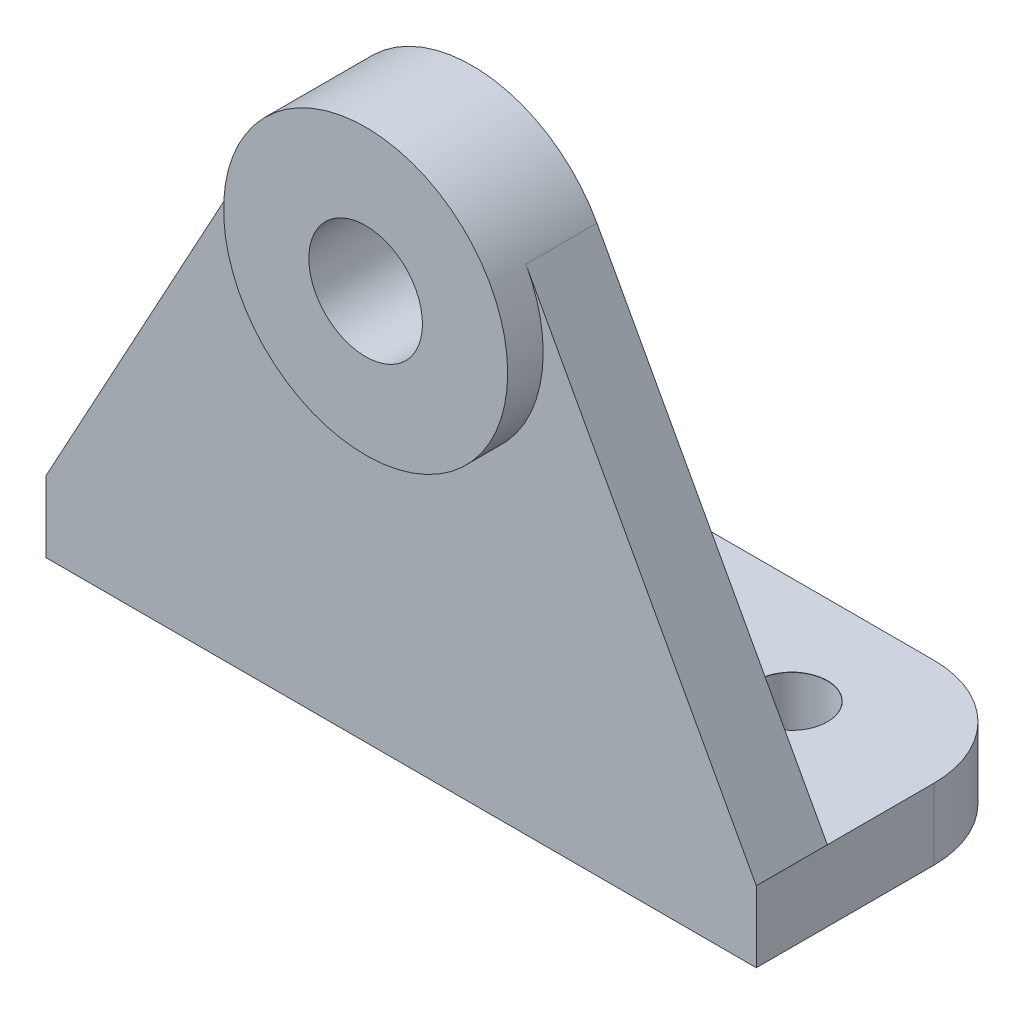
SolidWorks part; units mm, degrees
material "AISI 304"
ref_plane "Front Plane" through (0, 0, 0) normal (0, 0, 1) x (1, 0, 0)
ref_plane "Top Plane" through (0, 0, 0) normal (0, 1, 0) x (1, 0, 0)
ref_plane "Right Plane" through (0, 0, 0) normal (1, 0, 0) x (0, 0, -1)
sketch "Croquis1" plane through (0, 0, 0) normal (0, 1, 0) x (1, 0, 0)
  line L1 (50, -20) -> (-50, -20)
  line L2 (50, -20) -> (50, 20)
  line L3 (50, 20) -> (-50, 20)
  line L4 (-50, -20) -> (-50, 20)
  line L5 (50, -20) -> (-50, 20) construction
  line L6 (50, 20) -> (-50, -20) construction
  point P0 (0, 0)
  dimension "D1" = 40
  dimension "D2" = 100
extrude "Saliente-Extruir1" add sketch "Croquis1" along normal blind 10
sketch "Croquis2" plane through (0, 0, 20) normal (0, 0, 1) x (1, 0, 0)
  line L0 (0, 10) -> (0, 60) construction
  line L1 (-50, 10) -> (50, 10) construction
  line L2 (-50, 10) -> (-17.5647, 69.5647)
  line L3 (-50, 10) -> (50, 10)
  line L4 (50, 10) -> (17.5647, 69.5647)
  arc A0 (17.5647, 69.5647) -> (-17.5647, 69.5647) centre (0, 60) ccw
  circle A1 centre (0, 60) radius 8
  dimension "D2" = 20
  dimension "D3" = 16
  dimension "D1" = 50
extrude "Saliente-Extruir2" add sketch "Croquis2" against normal blind 10
sketch "Croquis3" plane through (0, 0, 20) normal (0, 0, 1) x (1, 0, 0)
  circle A0 centre (0, 60) radius 20
  circle A1 centre (0, 60) radius 8
extrude "Saliente-Extruir3" add sketch "Croquis3" along normal blind 5
sketch "Croquis4" plane through (0, 10, 0) normal (0, 1, 0) x (1, 0, 0)
  line L0 (-17.5647, -20) -> (-50, -20) construction
  circle A0 centre (-30, 5) radius 5.0987
  point P0 (-30, 5)
  point P7 (-30, 5)
  point P9 (-30, 5)
  dimension "D1" = 30
  dimension "D2" = 25
hole_wizard "Ø9.8 (9.8) Diameter Hole1" positions "Croquis4" profile "Croquis5" hole size "Ø9.8" standard "ANSI Metric" end condition through all
sketch "Croquis5" plane through (-30, 10, -5) normal (1, 0, 0) x (0, 0, 1)
  line L0 (0, 0) -> (0, 10)
  line L1 (0, 10) -> (4.9, 10)
  line L2 (4.9, 10) -> (4.9, 0.021)
  line L3 (4.9, 0.021) -> (4.925, 0)
  line L5 (4.925, 0) -> (0, 0)
  line L6 (-4.9, 0.021) -> (-4.925, 0) construction
  line L11 (0, -6.35) -> (0, 107.95) construction
  dimension "Thru Hole Dia." = 9.8
  dimension "Thru Hole Depth" = 10
  dimension "Near C'Sink Dia." = 9.85
  dimension "Near C'Sink Angle" = 100
sketch "Croquis6" plane through (0, 10, 0) normal (0, 1, 0) x (1, 0, 0)
  line L0 (50, -20) -> (17.5647, -20) construction
  circle A0 centre (30, 5) radius 4.856
  point P0 (30, 5)
  dimension "D1" = 25
  dimension "D2" = 30
hole_wizard "Ø10.0 (10) Diameter Hole1" positions "Croquis6" profile "Croquis7" hole size "Ø10.0" standard "ANSI Metric" end condition through all
sketch "Croquis7" plane through (30, 10, -5) normal (1, 0, 0) x (0, 0, 1)
  line L0 (0, 0) -> (0, 10)
  line L1 (0, 10) -> (5, 10)
  line L2 (5, 10) -> (5, 0.021)
  line L3 (5, 0.021) -> (5.025, 0)
  line L5 (5.025, 0) -> (0, 0)
  line L6 (-5, 0.021) -> (-5.025, 0) construction
  line L11 (0, -6.35) -> (0, 107.95) construction
  dimension "Thru Hole Dia." = 10
  dimension "Thru Hole Depth" = 10
  dimension "Near C'Sink Dia." = 10.05
  dimension "Near C'Sink Angle" = 100
fillet "Redondeo1" radius 15 2 edges at (50, 5, -20) (-50, 5, -20)
